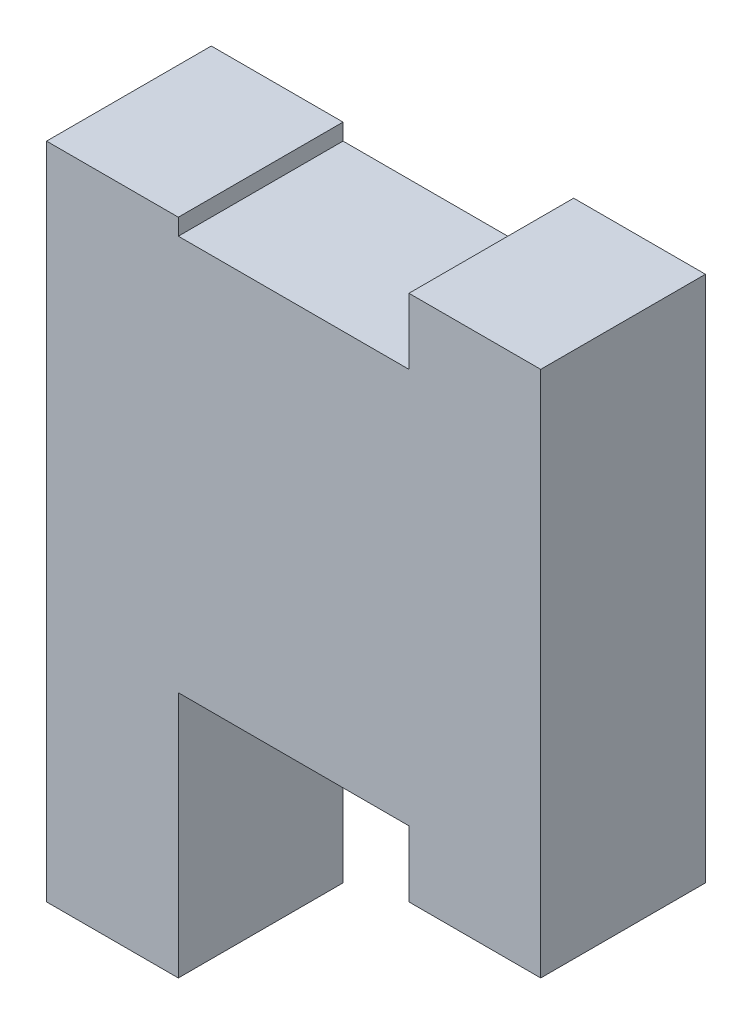
SolidWorks part; units mm, degrees
material "PBT General Purpose"
ref_plane "Front Plane" through (0, 0, 0) normal (0, 0, 1) x (1, 0, 0)
ref_plane "Top Plane" through (0, 0, 0) normal (0, 1, 0) x (1, 0, 0)
ref_plane "Right Plane" through (0, 0, 0) normal (1, 0, 0) x (0, 0, -1)
sketch "frame_outline" plane through (0, 0, 0) normal (0, 0, 1) x (1, 0, 0)
  line L110 (0, 0) -> (0, 1)
  line L111 (0, 1) -> (0.2, 1)
  line L112 (0.2, 1) -> (0.2, 0.975)
  line L113 (0.2, 0.975) -> (0.55, 0.975)
  line L114 (0.55, 0.975) -> (0.55, 1.075)
  line L115 (0.55, 1.075) -> (0.75, 1.075)
  line L116 (0.75, 1.075) -> (0.75, 0.275)
  line L117 (0.75, 0.275) -> (0.55, 0.275)
  line L118 (0.55, 0.275) -> (0.55, 0.375)
  line L119 (0.55, 0.375) -> (0.2, 0.375)
  line L120 (0.2, 0.375) -> (0.2, 0)
  line L121 (0.2, 0) -> (0, 0)
  line L122 (0.75, 0.675) -> (0.1351, 0.675) construction
  line L123 (0.55, 0.975) -> (0.55, 0.375) construction
  point P11 (0.55, 0.675)
  dimension "D1" = 1
  dimension "D2" = 0.2
  dimension "D3" = 0.35
  dimension "D4" = 0.2
  dimension "D5" = 0.6
  dimension "D6" = 0.8
  dimension "D7" = 0.325
extrude "Boss-Extrude1" add sketch "frame_outline" along normal mid plane 0.25
equation "\"t\"= 0.25'thickness of the sheets"
equation "\"t_cf\" = 0.115'thickness of single carbon fiber layer"
equation "\"t_kapton\" = 0.025'thickness of single Kapton flex layer"
equation "\"t_fr4\" = 0.1'thickness of FR4 with copper layer"
equation "\"joint_flex\"= 0.1'Width of flextures gap"
equation "\"joint_flex_eff\"= 0.02'Width of flecture after castelation"
equation "\"joint_fold\"= 0.2'Width of folding joints for 90deg fold"
equation "\"gap_tolerance\"= 0.002'Width to have interfecence fit between carbon fiber inserts"
equation "\"assemble_angle\"= 90'Angle of assembly parts"
equation "\"D1@Boss-Extrude1\"=\"t\""
equation "\"link_lift\"= 0.5'Actuation linkage amplification for the lift motion"
equation "\"link_swing\"= 0.45'Actuation linkage amplification for the swing motion"
equation "\"D7@frame_outline\"=\"link_swing\"-\"t\"/2"
